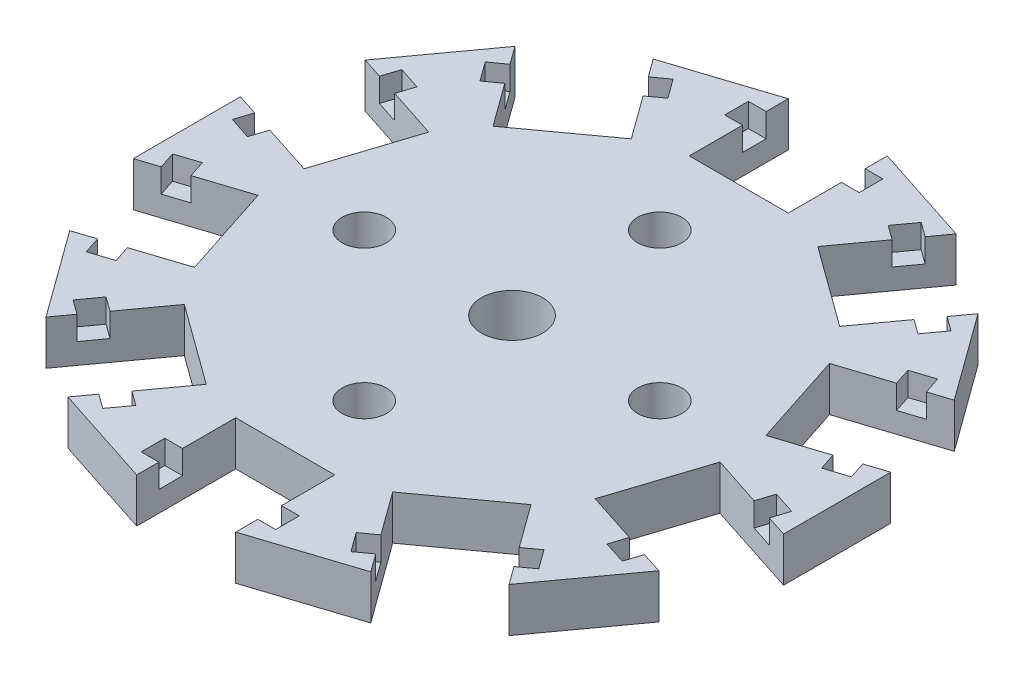
SolidWorks part; units mm, degrees
ref_plane "Front Plane" through (0, 0, 0) normal (0, 0, 1) x (1, 0, 0)
ref_plane "Top Plane" through (0, 0, 0) normal (0, 1, 0) x (1, 0, 0)
ref_plane "Right Plane" through (0, 0, 0) normal (1, 0, 0) x (0, 0, -1)
sketch "Sketch1" plane through (0, 0, 0) normal (0, 1, 0) x (1, 0, 0)
  line L1 (0, 23.1322) -> (-13.5967, 18.7143)
  line L2 (-13.5967, 18.7143) -> (-22, 7.1482)
  line L3 (-22, 7.1482) -> (-22, -7.1482)
  line L4 (-22, -7.1482) -> (-13.5967, -18.7143)
  line L5 (-13.5967, -18.7143) -> (0, -23.1322)
  line L6 (0, -23.1322) -> (13.5967, -18.7143)
  line L7 (13.5967, -18.7143) -> (22, -7.1482)
  line L8 (22, -7.1482) -> (22, 7.1482)
  line L9 (22, 7.1482) -> (13.5967, 18.7143)
  line L10 (13.5967, 18.7143) -> (0, 23.1322)
  circle A0 centre (0, 0) radius 22 construction
  dimension "D1" = 44
extrude "Boss-Extrude1" add sketch "Sketch1" along normal blind 3
sketch "Sketch2" plane through (0, 3, 0) normal (0, 1, 0) x (1, 0, 0)
  line L0 (0, 23.1322) -> (-3.35, 22.0437)
  line L1 (0, 23.1322) -> (-13.5967, 18.7143) construction
  line L2 (-3.35, 22.0437) -> (-3.35, 15.3437)
  line L3 (-3.35, 15.3437) -> (3.35, 15.3437)
  line L4 (3.35, 15.3437) -> (3.35, 22.0437)
  line L5 (13.5967, 18.7143) -> (0, 23.1322) construction
  line L6 (3.35, 22.0437) -> (0, 23.1322)
  line L7 (11.729, 10.4442) -> (15.6672, 15.8646)
  line L8 (15.6672, 15.8646) -> (13.5967, 18.7143)
  line L9 (13.5967, 18.7143) -> (10.2467, 19.8028)
  line L10 (10.2467, 19.8028) -> (6.3086, 14.3824)
  line L11 (6.3086, 14.3824) -> (11.729, 10.4442)
  line L12 (15.6279, 1.5554) -> (22, 3.6258)
  line L13 (22, 3.6258) -> (22, 7.1482)
  line L14 (22, 7.1482) -> (19.9296, 9.9979)
  line L15 (19.9296, 9.9979) -> (13.5575, 7.9275)
  line L16 (13.5575, 7.9275) -> (15.6279, 1.5554)
  line L17 (13.5575, -7.9275) -> (19.9296, -9.9979)
  line L18 (19.9296, -9.9979) -> (22, -7.1482)
  line L19 (22, -7.1482) -> (22, -3.6258)
  line L20 (22, -3.6258) -> (15.6279, -1.5554)
  line L21 (15.6279, -1.5554) -> (13.5575, -7.9275)
  line L22 (6.3086, -14.3824) -> (10.2467, -19.8028)
  line L23 (10.2467, -19.8028) -> (13.5967, -18.7143)
  line L24 (13.5967, -18.7143) -> (15.6672, -15.8646)
  line L25 (15.6672, -15.8646) -> (11.729, -10.4442)
  line L26 (11.729, -10.4442) -> (6.3086, -14.3824)
  line L27 (-3.35, -15.3437) -> (-3.35, -22.0437)
  line L28 (-3.35, -22.0437) -> (0, -23.1322)
  line L29 (0, -23.1322) -> (3.35, -22.0437)
  line L30 (3.35, -22.0437) -> (3.35, -15.3437)
  line L31 (3.35, -15.3437) -> (-3.35, -15.3437)
  line L32 (-11.729, -10.4442) -> (-15.6672, -15.8646)
  line L33 (-15.6672, -15.8646) -> (-13.5967, -18.7143)
  line L34 (-13.5967, -18.7143) -> (-10.2467, -19.8028)
  line L35 (-10.2467, -19.8028) -> (-6.3086, -14.3824)
  line L36 (-6.3086, -14.3824) -> (-11.729, -10.4442)
  line L37 (-15.6279, -1.5554) -> (-22, -3.6258)
  line L38 (-22, -3.6258) -> (-22, -7.1482)
  line L39 (-22, -7.1482) -> (-19.9296, -9.9979)
  line L40 (-19.9296, -9.9979) -> (-13.5575, -7.9275)
  line L41 (-13.5575, -7.9275) -> (-15.6279, -1.5554)
  line L42 (-13.5575, 7.9275) -> (-19.9296, 9.9979)
  line L43 (-19.9296, 9.9979) -> (-22, 7.1482)
  line L44 (-22, 7.1482) -> (-22, 3.6258)
  line L45 (-22, 3.6258) -> (-15.6279, 1.5554)
  line L46 (-15.6279, 1.5554) -> (-13.5575, 7.9275)
  line L47 (-6.3086, 14.3824) -> (-10.2467, 19.8028)
  line L48 (-10.2467, 19.8028) -> (-13.5967, 18.7143)
  line L49 (-13.5967, 18.7143) -> (-15.6672, 15.8646)
  line L50 (-15.6672, 15.8646) -> (-11.729, 10.4442)
  line L51 (-11.729, 10.4442) -> (-6.3086, 14.3824)
  point P5 (0, 15.3437)
  point P59 (0, 0)
  dimension "D1" = 6.7
  dimension "D2" = 6.7
  dimension "D3" = 10
extrude "Cut-Extrude1" cut sketch "Sketch2" against normal up to surface (3 mm away) up to face at (0, 0, 0)
sketch "Sketch7" plane through (0, 3, 0) normal (0, 1, 0) x (1, 0, 0)
  circle A0 centre (0, 0) radius 10 construction
  circle A1 centre (0, 10) radius 1.5
  circle A2 centre (10, 0) radius 1.5
  circle A3 centre (0, -10) radius 1.5
  circle A4 centre (-10, 0) radius 1.5
  dimension "D1" = 20
  dimension "D2" = 3
extrude "Cut-Extrude3" cut sketch "Sketch7" against normal up to surface (3 mm away) up to face at (0, 0, 0)
sketch "Sketch4" plane through (0, 3, 0) normal (0, 1, 0) x (1, 0, 0)
  line L0 (-3.35, 15.3437) -> (3.35, 15.3437) construction
  line L1 (-4.55, 18.9437) -> (4.55, 18.9437)
  line L2 (-4.55, 18.9437) -> (-4.55, 20.5437)
  line L3 (-4.55, 20.5437) -> (4.55, 20.5437)
  line L4 (4.55, 18.9437) -> (4.55, 20.5437)
  line L5 (-4.55, 18.9437) -> (4.55, 20.5437) construction
  line L6 (-4.55, 20.5437) -> (4.55, 18.9437) construction
  line L7 (7.4538, 18.0002) -> (8.3942, 19.2946)
  line L8 (7.4538, 18.0002) -> (14.8158, 12.6513)
  line L9 (14.8158, 12.6513) -> (15.7563, 13.9458)
  line L10 (8.3942, 19.2946) -> (15.7563, 13.9458)
  line L11 (16.6105, 10.1812) -> (18.1322, 10.6757)
  line L12 (16.6105, 10.1812) -> (19.4225, 1.5266)
  line L13 (19.4225, 1.5266) -> (20.9442, 2.021)
  line L14 (18.1322, 10.6757) -> (20.9442, 2.021)
  line L15 (19.4225, -1.5266) -> (20.9442, -2.021)
  line L16 (19.4225, -1.5266) -> (16.6105, -10.1812)
  line L17 (16.6105, -10.1812) -> (18.1322, -10.6757)
  line L18 (20.9442, -2.021) -> (18.1322, -10.6757)
  line L19 (14.8158, -12.6513) -> (15.7563, -13.9458)
  line L20 (14.8158, -12.6513) -> (7.4538, -18.0002)
  line L21 (7.4538, -18.0002) -> (8.3942, -19.2946)
  line L22 (15.7563, -13.9458) -> (8.3942, -19.2946)
  line L23 (4.55, -18.9437) -> (4.55, -20.5437)
  line L24 (4.55, -18.9437) -> (-4.55, -18.9437)
  line L25 (-4.55, -18.9437) -> (-4.55, -20.5437)
  line L26 (4.55, -20.5437) -> (-4.55, -20.5437)
  line L27 (-7.4538, -18.0002) -> (-8.3942, -19.2946)
  line L28 (-7.4538, -18.0002) -> (-14.8158, -12.6513)
  line L29 (-14.8158, -12.6513) -> (-15.7563, -13.9458)
  line L30 (-8.3942, -19.2946) -> (-15.7563, -13.9458)
  line L31 (-16.6105, -10.1812) -> (-18.1322, -10.6757)
  line L32 (-16.6105, -10.1812) -> (-19.4225, -1.5266)
  line L33 (-19.4225, -1.5266) -> (-20.9442, -2.021)
  line L34 (-18.1322, -10.6757) -> (-20.9442, -2.021)
  line L35 (-19.4225, 1.5266) -> (-20.9442, 2.021)
  line L36 (-19.4225, 1.5266) -> (-16.6105, 10.1812)
  line L37 (-16.6105, 10.1812) -> (-18.1322, 10.6757)
  line L38 (-20.9442, 2.021) -> (-18.1322, 10.6757)
  line L39 (-14.8158, 12.6513) -> (-15.7563, 13.9458)
  line L40 (-14.8158, 12.6513) -> (-7.4538, 18.0002)
  line L41 (-7.4538, 18.0002) -> (-8.3942, 19.2946)
  line L42 (-15.7563, 13.9458) -> (-8.3942, 19.2946)
  point P0 (0, 19.7437)
  point P46 (0, 0)
  dimension "D1" = 9.1
  dimension "D2" = 1.6
  dimension "D3" = 4.4
  dimension "D4" = 10
extrude "Cut-Extrude2" cut sketch "Sketch4" against normal blind 1.6
sketch "Sketch10" plane through (0, 0, 0) normal (0, -1, 0) x (1, 0, 0)
  circle A0 centre (0, 0) radius 2.075
  dimension "D1" = 4.15
extrude "Cut-Extrude6" cut sketch "Sketch10" against normal up to surface (3 mm away) up to face at (0, 3, 0)
sketch "Sketch8" plane through (0, 0, 0) normal (0, -1, 0) x (1, 0, 0)
  circle A0 centre (0, 0) radius 13
  dimension "D1" = 26
extrude "Cut-Extrude4" [suppressed] cut sketch "Sketch8" against normal blind 1
sketch "Sketch9" plane through (0, 3, 0) normal (0, 1, 0) x (1, 0, 0)
  circle A0 centre (0, 10) radius 3.05
  circle A1 centre (10, 0) radius 3.05
  circle A2 centre (0, -10) radius 3.05
  circle A3 centre (-10, 0) radius 3.05
  dimension "D1" = 6.1
extrude "Cut-Extrude5" [suppressed] cut sketch "Sketch9" against normal blind 1
equation "\"E\"=10"
